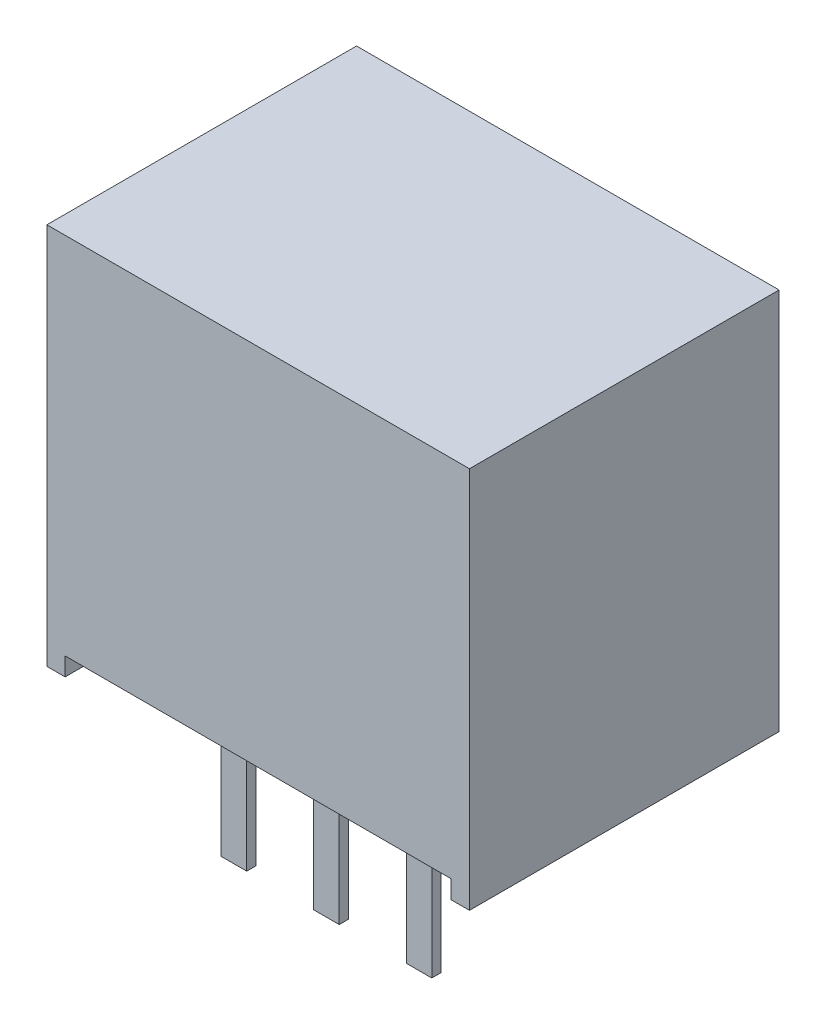
SolidWorks part; units mm, degrees
ref_plane "Front Plane" through (0, 0, 0) normal (0, 0, 1) x (1, 0, 0)
ref_plane "Top Plane" through (0, 0, 0) normal (0, 1, 0) x (1, 0, 0)
ref_plane "Right Plane" through (0, 0, 0) normal (1, 0, 0) x (0, 0, -1)
sketch "Sketch1" plane through (0, 0, 0) normal (0, 0, 1) x (1, 0, 0)
  line L1 (-5.8, -5.25) -> (5.8, -5.25)
  line L2 (-5.8, -5.25) -> (-5.8, 5.25)
  line L3 (-5.8, 5.25) -> (5.8, 5.25)
  line L4 (5.8, -5.25) -> (5.8, 5.25)
  line L5 (-5.8, -5.25) -> (5.8, 5.25) construction
  line L6 (-5.8, 5.25) -> (5.8, -5.25) construction
  point P0 (0, 0)
  dimension "D1" = 10.5
  dimension "D2" = 11.6
extrude "Boss-Extrude1" add sketch "Sketch1" along normal mid plane 8.5 contours L3 L4 L1 L2
sketch "Sketch2" plane through (0, 0, 4.25) normal (0, 0, 1) x (1, 0, 0)
  line L0 (-5.8, -5.25) -> (5.8, -5.25) construction
  line L1 (-5.3, -5.25) -> (5.3, -5.25)
  line L2 (-5.3, -5.25) -> (-5.3, -4.75)
  line L3 (-5.3, -4.75) -> (5.3, -4.75)
  line L4 (5.3, -5.25) -> (5.3, -4.75)
  line L5 (-5.8, -5.25) -> (-5.8, 5.25) construction
  line L6 (5.8, -5.25) -> (5.8, 5.25) construction
  dimension "D1" = 0.5
  dimension "D2" = 0.5
  dimension "D3" = 0.5
extrude "Cut-Extrude1" cut sketch "Sketch2" against normal through all
sketch "Sketch3" plane through (0, -4.75, 0) normal (0, -1, 0) x (-1, 0, 0)
  line L0 (0, -2.25) -> (0, 0) construction
  line L1 (0.35, -2.375) -> (-0.35, -2.375)
  line L2 (0.35, -2.375) -> (0.35, -2.125)
  line L3 (0.35, -2.125) -> (-0.35, -2.125)
  line L4 (-0.35, -2.375) -> (-0.35, -2.125)
  line L5 (0.35, -2.375) -> (-0.35, -2.125) construction
  line L6 (0.35, -2.125) -> (-0.35, -2.375) construction
  line L7 (-5.3, -4.25) -> (5.3, -4.25) construction
  line L9 (2.89, -2.125) -> (2.19, -2.125)
  line L10 (2.89, -2.125) -> (2.89, -2.375)
  line L11 (2.89, -2.375) -> (2.19, -2.375)
  line L12 (2.19, -2.125) -> (2.19, -2.375)
  line L13 (2.89, -2.125) -> (2.19, -2.375) construction
  line L14 (2.89, -2.375) -> (2.19, -2.125) construction
  line L15 (-2.89, -2.125) -> (-2.19, -2.125)
  line L16 (-2.89, -2.125) -> (-2.89, -2.375)
  line L17 (-2.89, -2.375) -> (-2.19, -2.375)
  line L18 (-2.19, -2.125) -> (-2.19, -2.375)
  line L19 (-2.89, -2.125) -> (-2.19, -2.375) construction
  line L20 (-2.89, -2.375) -> (-2.19, -2.125) construction
  point P0 (0, -2.25)
  point P10 (2.54, -2.25)
  point P15 (-2.54, -2.25)
  dimension "D1" = 0.7
  dimension "D2" = 0.25
  dimension "D3" = 2
  dimension "D4" = 2.54
  dimension "D5" = 2.54
  dimension "D6" = 0.7
  dimension "D7" = 0.25
  dimension "D8" = 0.7
  dimension "D9" = 0.25
extrude "Boss-Extrude2" add sketch "Sketch3" along normal blind 4.5
